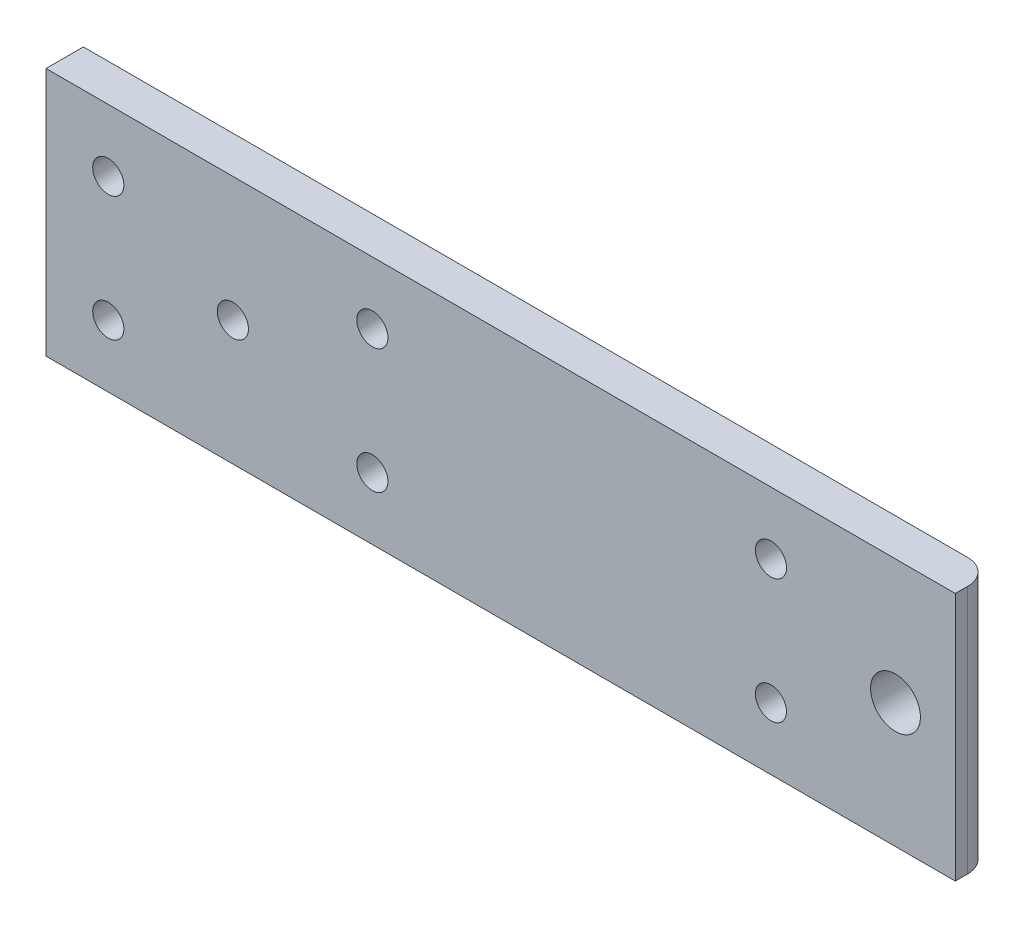
SolidWorks part; units mm, degrees
ref_plane "Спереди" through (0, 0, 0) normal (0, 0, 1) x (1, 0, 0)
ref_plane "Сверху" through (0, 0, 0) normal (0, 1, 0) x (1, 0, 0)
ref_plane "Справа" through (0, 0, 0) normal (1, 0, 0) x (0, 0, -1)
sketch "Эскиз1" plane through (0, 0, 0) normal (0, 1, 0) x (1, 0, 0)
  line L0 (168.311, -12.1554) -> (168.311, -15.1554)
  line L13 (168.311, -12.1554) -> (241.311, -12.1554)
  line L14 (241.311, -12.1554) -> (241.311, -15.1554)
  line L15 (241.311, -15.1554) -> (168.311, -15.1554)
  dimension "D1" = 73
extrude "Бобышка-Вытянуть1" add sketch "Эскиз1" along normal blind 20 contours L13 L14 L15 L0
sketch "Эскиз2" plane through (0, 0, 12.1554) normal (0, 0, -1) x (-1, 0, 0)
  line L0 (-194.511, 15) -> (-173.311, 15) construction
  line L1 (-173.311, 15) -> (-173.311, 5) construction
  line L2 (-173.311, 5) -> (-173.311, 10)
  line L3 (-139.311, 15) -> (-194.511, 15) construction
  line L4 (5.489, 10) -> (-264.511, 10) construction
  line L5 (-173.311, 10) -> (-183.311, 10) construction
  line L6 (-139.311, 5) -> (-194.511, 5) construction
  line L7 (-168.311, 20) -> (-168.311, 0) construction
  line L8 (-194.511, 15) -> (-226.511, 15) construction
  line L9 (-226.511, 15) -> (-226.511, 5) construction
  line L10 (-226.511, 10) -> (-236.511, 10)
  circle A0 centre (-173.311, 15) radius 1.25
  circle A1 centre (-183.311, 10) radius 1.25
  circle A2 centre (-173.311, 5) radius 1.25
  circle A3 centre (-236.511, 10) radius 2
  circle A9 centre (-194.511, 15) radius 1.25
  circle A10 centre (-194.511, 5) radius 1.25
  circle A13 centre (-226.511, 15) radius 1.25
  circle A14 centre (-226.511, 5) radius 1.25
  dimension "D1" = 21.2
  dimension "D7" = 5
  dimension "D2" = 5
  dimension "D3" = 5
  dimension "D4" = 10
  dimension "D9" = 32
extrude "Вырез-Вытянуть1" cut sketch "Эскиз2" against normal blind 20
fillet "Скругление1" radius 2 1 edges at (241.311, 10, 12.1554)
